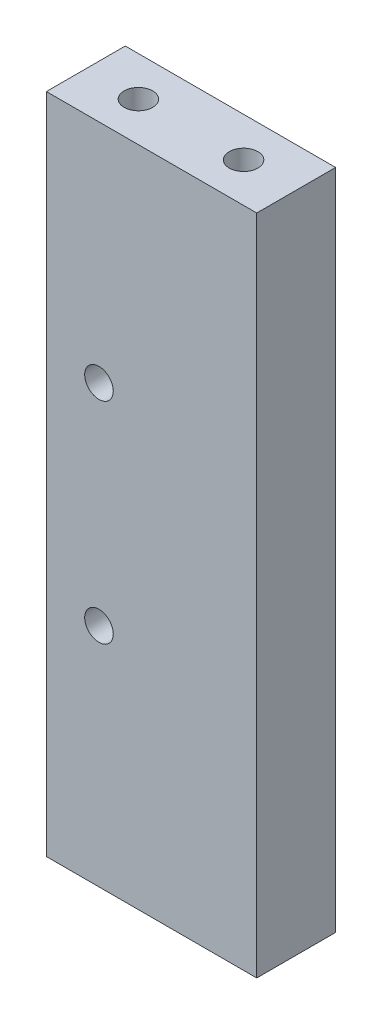
SolidWorks part; units mm, degrees
ref_plane "Front Plane" through (0, 0, 0) normal (0, 0, 1) x (1, 0, 0)
ref_plane "Top Plane" through (0, 0, 0) normal (0, 1, 0) x (1, 0, 0)
ref_plane "Right Plane" through (0, 0, 0) normal (1, 0, 0) x (0, 0, -1)
sketch "Sketch1" plane through (0, 0, 0) normal (0, 1, 0) x (1, 0, 0)
  line L1 (-27.3389, 9.525) -> (-1.9389, 9.525)
  line L2 (-27.3389, 9.525) -> (-27.3389, 0)
  line L3 (-27.3389, 0) -> (-1.9389, 0)
  line L4 (-1.9389, 9.525) -> (-1.9389, 0)
  dimension "D1" = 9.525
  dimension "D2" = 25.4
extrude "Boss-Extrude1" add sketch "Sketch1" along normal blind 80
hole_wizard "#8-32 Tapped Hole1" positions "Sketch3" profile "Sketch2" tap size "#8-32" standard "ANSI Inch"
sketch "Sketch3" plane through (0, 80, 0) normal (0, 1, 0) x (1, 0, 0)
  line L0 (-27.3389, 9.525) -> (-27.3389, 0) construction
  line L1 (-27.3389, 0) -> (-1.9389, 0) construction
  point P0 (-8.2889, 4.7625)
  point P2 (-20.9889, 4.7625)
  dimension "D1" = 12.7
  dimension "D2" = 6.35
  dimension "D3" = 4.7625
sketch "Sketch2" plane through (-8.2889, 80, -4.7625) normal (1, 0, 0) x (0, 0, 1)
  line L0 (0, 0) -> (0, 20.0878)
  line L1 (0, 20.0878) -> (1.7272, 19.05)
  line L2 (1.7272, 19.05) -> (1.7272, 0)
  line L5 (1.7272, 0) -> (0, 0)
  line L10 (0, 20.0878) -> (-1.7272, 19.05) construction
  line L11 (0, -6.35) -> (0, 107.95) construction
  dimension "Tap Drill Dia." = 3.4544
  dimension "Tap Drill Depth" = 19.05
  dimension "Drill Angle" = 118
cosmetic thread "Hole Thread1" parameters "D1"=15.875, "D2"=4.1656
cosmetic thread "Hole Thread2" parameters "D1"=15.875, "D2"=4.1656
hole_wizard "#8-32 Tapped Hole2" positions "Sketch5" profile "Sketch4" tap size "#8-32" standard "ANSI Inch"
sketch "Sketch5" plane through (0, 0, 0) normal (0, -1, 0) x (-1, 0, 0)
  line L0 (27.3389, 9.525) -> (27.3389, 0) construction
  line L1 (27.3389, 0) -> (1.9389, 0) construction
  point P0 (20.9889, 4.7625)
  point P2 (8.2889, 4.7625)
  dimension "D1" = 12.7
  dimension "D2" = 6.35
  dimension "D3" = 4.7625
sketch "Sketch4" plane through (-20.9889, 0, -4.7625) normal (1, 0, 0) x (0, 0, -1)
  line L0 (0, 0) -> (0, 21.1038)
  line L1 (0, 21.1038) -> (1.7272, 20.066)
  line L2 (1.7272, 20.066) -> (1.7272, 0)
  line L5 (1.7272, 0) -> (0, 0)
  line L10 (0, 21.1038) -> (-1.7272, 20.066) construction
  line L11 (0, -6.35) -> (0, 107.95) construction
  dimension "Tap Drill Dia." = 3.4544
  dimension "Tap Drill Depth" = 20.066
  dimension "Drill Angle" = 118
cosmetic thread "Hole Thread3" parameters "D1"=16.002, "D2"=4.1656
cosmetic thread "Hole Thread4" parameters "D1"=16.002, "D2"=4.1656
hole_wizard "#8-32 Tapped Hole3" positions "Sketch7" profile "Sketch6" tap size "#8-32" standard "ANSI Inch" end condition through all
sketch "Sketch7" plane through (0, 0, 0) normal (0, 0, 1) x (1, 0, 0)
  line L0 (-27.3389, 0) -> (-1.9389, 0) construction
  line L2 (-27.3389, 80) -> (-27.3389, 0) construction
  point P0 (-20.9889, 52.705)
  point P2 (-20.9889, 27.305)
  dimension "D1" = 25.4
  dimension "D2" = 27.305
  dimension "D3" = 6.35
sketch "Sketch6" plane through (-20.9889, 52.705, 0) normal (1, 0, 0) x (0, -1, 0)
  line L0 (0, 0) -> (0, 9.525)
  line L1 (0, 9.525) -> (1.7272, 9.525)
  line L2 (1.7272, 9.525) -> (1.7272, 0)
  line L5 (1.7272, 0) -> (0, 0)
  line L11 (0, -6.35) -> (0, 107.95) construction
  dimension "Thru Tap Drill Dia." = 3.4544
  dimension "Thru Tap Drill Depth" = 9.525
cosmetic thread "Hole Thread5" parameters "D2"=4.1656
cosmetic thread "Hole Thread6" parameters "D2"=4.1656
